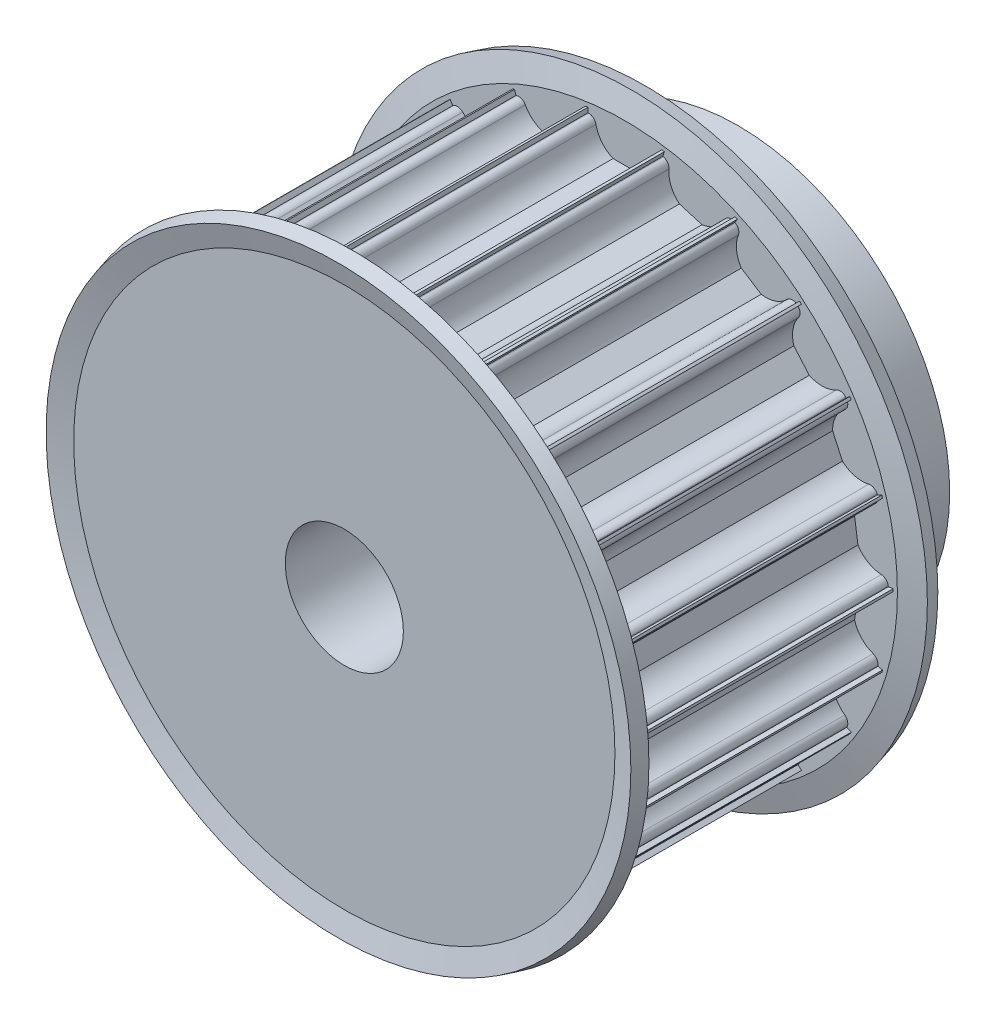
SolidWorks part; units mm, degrees
ref_plane "Front Plane" through (0, 0, 0) normal (0, 0, 1) x (1, 0, 0)
ref_plane "Top Plane" through (0, 0, 0) normal (0, 1, 0) x (1, 0, 0)
ref_plane "Right Plane" through (0, 0, 0) normal (1, 0, 0) x (0, 0, -1)
sketch "Sketch1" plane through (0, 0, 0) normal (1, 0, 0) x (0, 0, -1)
  line L0 (0, 0) -> (57.2771, 0) construction
  line L1 (0, 6) -> (40, 6)
  line L2 (40, 6) -> (40, 21.5)
  line L3 (40, 21.5) -> (30, 21.5)
  line L4 (30, 21.5) -> (30, 27.25)
  line L5 (30, 27.25) -> (0, 27.25)
  line L6 (0, 27.25) -> (0, 6)
  dimension "D1" = 15.5
  dimension "D2" = 10
  dimension "D3" = 30
  dimension "D4" = 6
  dimension "D5" = 27.25
revolve "Revolve1" add sketch "Sketch1" angle 360 about L0
sketch "Sketch2" plane through (0, 0, 0) normal (0, 0, 1) x (1, 0, 0)
  line L0 (-3.6742, 26.5) -> (-3.75, 26.5)
  line L1 (-3.75, 26.5) -> (-3.75, 28.5)
  line L2 (-3.75, 28.5) -> (3.75, 28.5)
  line L3 (3.75, 28.5) -> (3.75, 26.5)
  line L4 (3.75, 26.5) -> (3.6742, 26.5)
  line L5 (-1.199, 23.75) -> (1.199, 23.75)
  arc A0 (2.9394, 25.9) -> (1.199, 23.75) centre (0, 26.5) cw
  arc A1 (2.9394, 25.9) -> (3.6742, 26.5) centre (3.6742, 25.75) cw
  arc A2 (-2.9394, 25.9) -> (-3.6742, 26.5) centre (-3.6742, 25.75) ccw
  arc A3 (-1.199, 23.75) -> (-2.9394, 25.9) centre (0, 26.5) cw
  point P12 (3, 26.5)
  point P15 (-3, 26.5)
  dimension "D1" = 3
  dimension "D5" = 0.75
  dimension "D2" = 26.5
  dimension "D3" = 7.5
  dimension "D4" = 2
  dimension "D6" = 2.75
extrude "Cut-Extrude1" cut sketch "Sketch2" against normal up to next
pattern_circular "CirPattern1" count 22 over 360 about axis through (0, 0, 0) along (0, 0, 1) of "Cut-Extrude1"
sketch "Sketch3" plane through (0, 0, 0) normal (1, 0, 0) x (0, 0, -1)
  line L0 (15, 26.4617) -> (15, -4.9005) construction
  line L1 (30, 26.4617) -> (0, 26.4617) construction
  line L2 (30, 21.5) -> (30, 27.4925)
  line L3 (30, 27.4925) -> (30.592, 29.7018)
  line L4 (30.592, 29.7018) -> (29.1431, 30.09)
  line L5 (29.1431, 30.09) -> (28.5, 27.69)
  line L6 (28.5, 27.69) -> (28.5, 21.5)
  line L7 (28.5, 21.5) -> (30, 21.5)
  line L8 (40, 21.5) -> (30, 21.5) construction
  line L9 (1.5, 27.69) -> (1.5, 21.5)
  line L10 (0.8569, 30.09) -> (1.5, 27.69)
  line L11 (-0.592, 29.7018) -> (0.8569, 30.09)
  line L12 (0, 27.4925) -> (-0.592, 29.7018)
  line L13 (0, 21.5) -> (0, 27.4925)
  line L14 (1.5, 21.5) -> (0, 21.5)
  line L15 (-85.5417, 0) -> (504.8473, 0) construction
  dimension "D1" = 15
  dimension "D2" = 6.19
  dimension "D3" = 2.4
  dimension "D4" = 1.5
revolve "Revolve2" add sketch "Sketch3" angle 360 about L15
